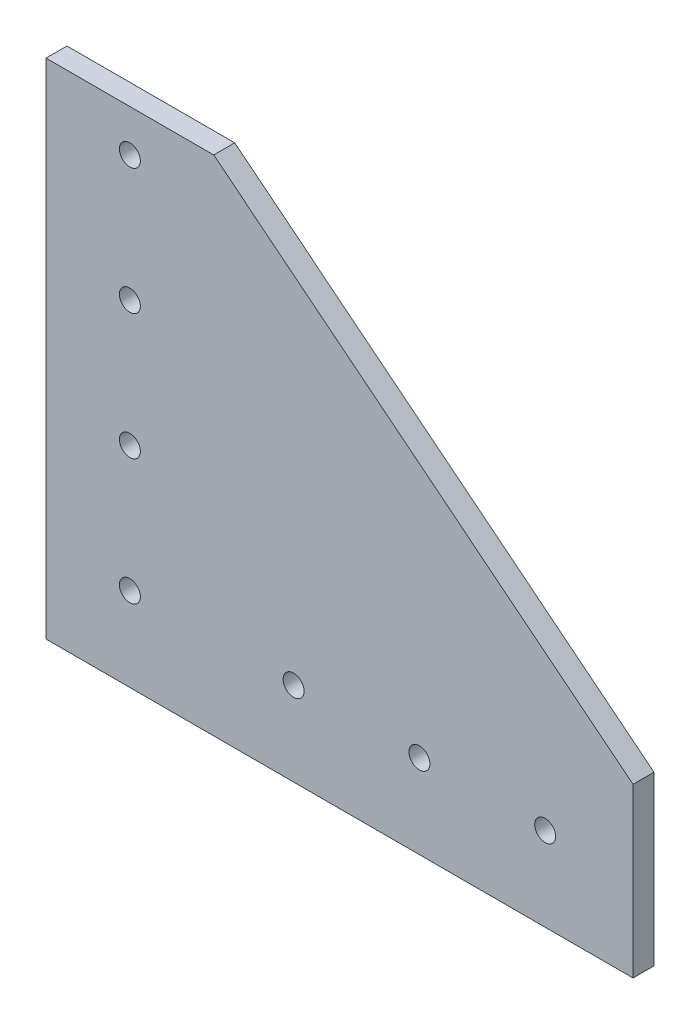
SolidWorks part; units mm, degrees
ref_plane "Front Plane" through (0, 0, 0) normal (0, 0, 1) x (1, 0, 0)
ref_plane "Top Plane" through (0, 0, 0) normal (0, 1, 0) x (1, 0, 0)
ref_plane "Right Plane" through (0, 0, 0) normal (1, 0, 0) x (0, 0, -1)
sketch "Sketch1" plane through (0, 0, 0) normal (0, 0, 1) x (1, 0, 0)
  line L0 (40.9099, -35.0656) -> (40.9099, -9.6656)
  line L1 (-47.9901, -35.0656) -> (40.9099, -35.0656)
  line L2 (-47.9901, -35.0656) -> (-47.9901, 41.1344)
  line L4 (-47.9901, 41.1344) -> (-22.5901, 41.1344)
  line L5 (-22.5901, 41.1344) -> (40.9099, -9.6656)
  point P0 (0, 0)
  dimension "D1" = 76.2
  dimension "D2" = 88.9
  dimension "D3" = 25.4
  dimension "D4" = 25.4
extrude "Boss-Extrude1" add sketch "Sketch1" along normal blind 3.175
sketch "Sketch2" plane through (0, 0, 0) normal (0, 0, -1) x (-1, 0, 0)
  line L0 (35.8949, -22.3656) -> (10.4949, -22.3656) construction
  line L1 (47.9901, -35.0656) -> (35.2901, -35.0656) construction
  line L2 (47.9901, -35.0656) -> (47.9901, -22.3656) construction
  line L3 (47.9901, -22.3656) -> (35.2901, -22.3656) construction
  line L4 (35.2901, -35.0656) -> (35.2901, -22.3656) construction
  circle A0 centre (35.2901, -22.3656) radius 1.5875
  circle A1 centre (35.2901, -3.3156) radius 1.5875
  circle A2 centre (35.2901, 15.7344) radius 1.5875
  circle A3 centre (35.2901, 34.7844) radius 1.5875
  circle A4 centre (10.4949, -22.3656) radius 1.5875
  circle A5 centre (-8.5551, -22.3656) radius 1.5875
  circle A6 centre (-27.6051, -22.3656) radius 1.5875
  dimension "D2" = 4
  dimension "D5" = 3.175
  dimension "D1" = 12.7
  dimension "D3" = 12.7
  dimension "D4" = 25.4
  dimension "D6" = 3
extrude "Cut-Extrude1" cut sketch "Sketch2" against normal through all
